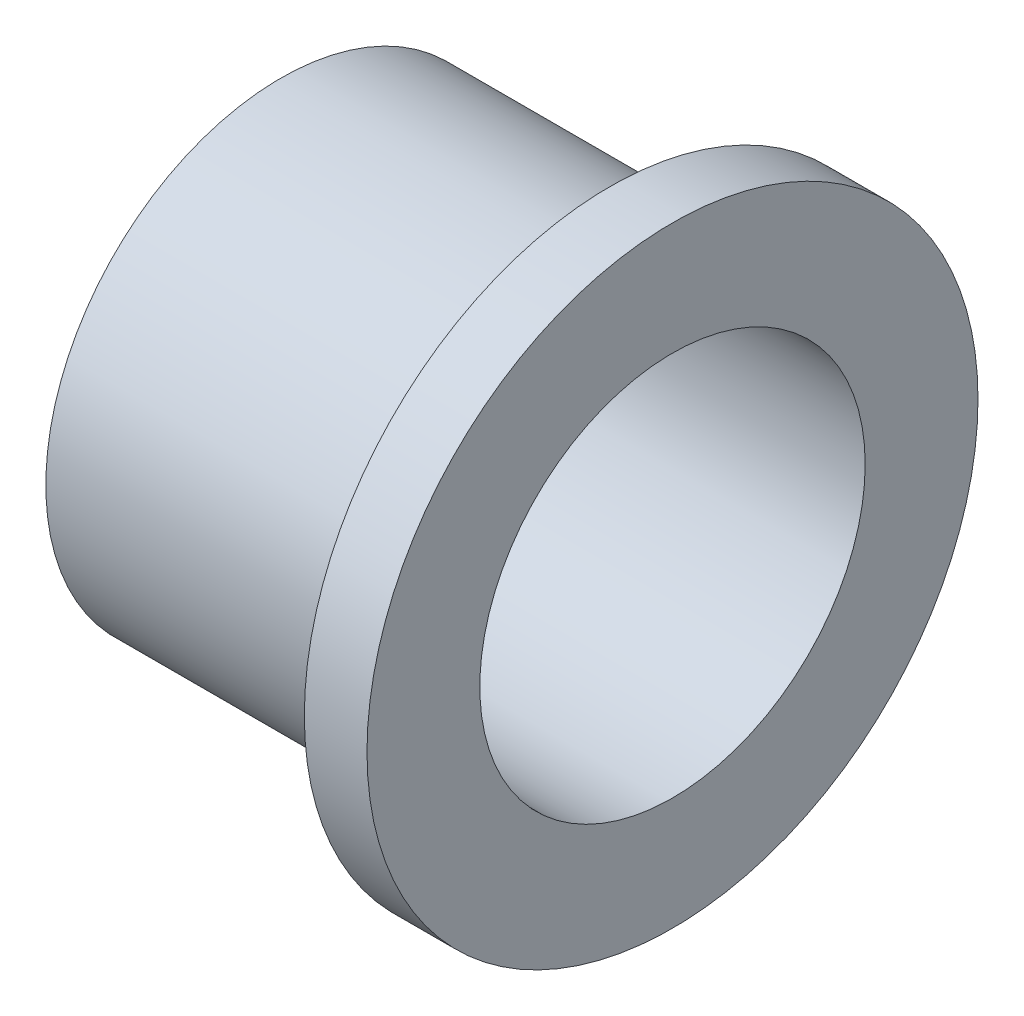
SolidWorks part; units mm, degrees
material "45"
ref_plane "前视基准面" through (0, 0, 0) normal (0, 0, 1) x (1, 0, 0)
ref_plane "上视基准面" through (0, 0, 0) normal (0, 1, 0) x (1, 0, 0)
ref_plane "右视基准面" through (0, 0, 0) normal (1, 0, 0) x (0, 0, -1)
sketch "草图1" plane through (0, 0, 0) normal (1, 0, 0) x (0, 0, -1)
  circle A0 centre (0, 0) radius 3
  circle A1 centre (0, 0) radius 2.46
  dimension "D1" = 4.92
  dimension "D2" = 6
extrude "凸台-拉伸1" add sketch "草图1" along normal blind 5
sketch "草图2" plane through (5, 0, 0) normal (1, 0, 0) x (0, 0, -1)
  circle A0 centre (0, 0) radius 2.46
  circle A1 centre (0, 0) radius 3.9
  dimension "D1" = 7.8
extrude "凸台-拉伸2" add sketch "草图2" against normal blind 0.8
